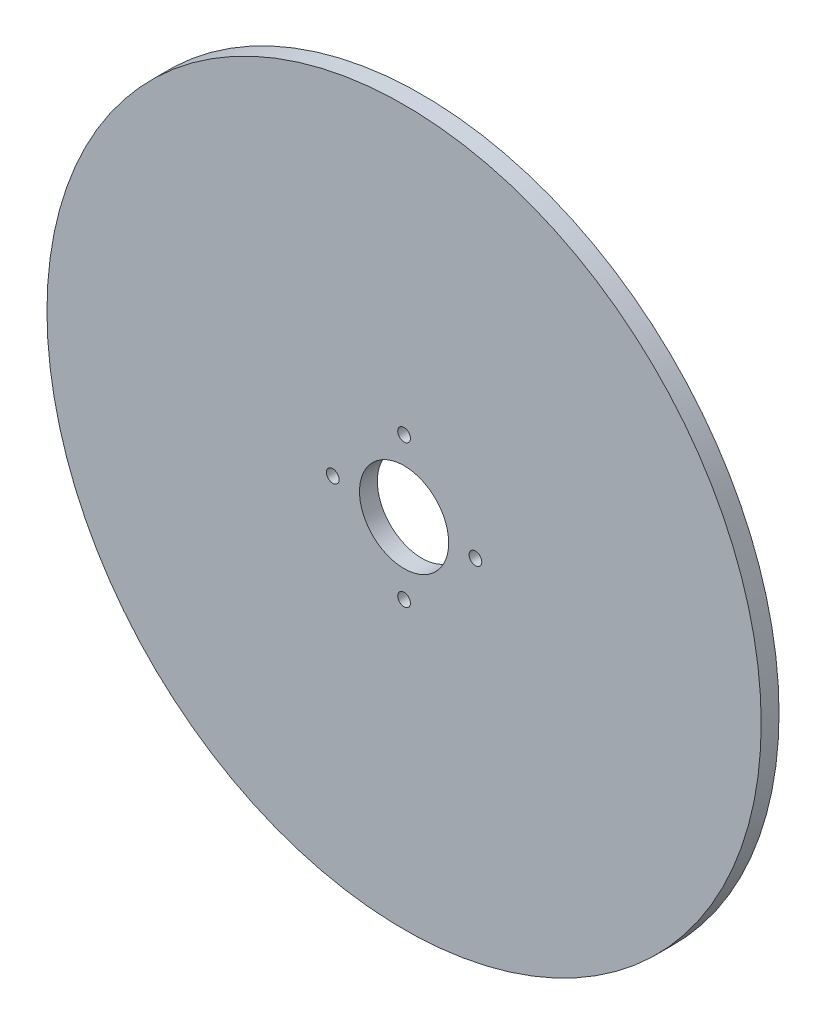
SolidWorks part; units mm, degrees
material "6061 Alloy"
ref_plane "Front Plane" through (0, 0, 0) normal (0, 0, 1) x (1, 0, 0)
ref_plane "Top Plane" through (0, 0, 0) normal (0, 1, 0) x (1, 0, 0)
ref_plane "Right Plane" through (0, 0, 0) normal (1, 0, 0) x (0, 0, -1)
sketch "Sketch1" plane through (0, 0, 0) normal (0, 0, 1) x (1, 0, 0)
  circle A0 centre (0, 0) radius 63.5762
  circle A1 centre (0, 0) radius 7.9375
  dimension "D1" = 127.1524
  dimension "D2" = 15.875
extrude "Boss-Extrude1" add sketch "Sketch1" along normal blind 3.175
hole_wizard "Tap Drill for #4-40 Tap1" positions "Sketch2" profile "Sketch3" hole size "#4-40" standard "ANSI Inch"
sketch "Sketch2" plane through (0, 0, 3.175) normal (0, 0, 1) x (1, 0, 0)
  point P0 (0, 12.7)
  point P2 (0, -12.7)
  point P4 (12.7, 0)
  point P6 (-12.7, 0)
  dimension "D1" = 12.7
  dimension "D2" = 12.7
  dimension "D3" = 12.7
  dimension "D4" = 12.7
sketch "Sketch3" plane through (0, 12.7, 3.175) normal (1, 0, 0) x (0, -1, 0)
  line L0 (0, 0) -> (0, 4.6792)
  line L1 (0, 4.6792) -> (1.1303, 4)
  line L2 (1.1303, 4) -> (1.1303, 0)
  line L5 (1.1303, 0) -> (0, 0)
  line L10 (0, 4.6792) -> (-1.1303, 4) construction
  line L11 (0, -6.35) -> (0, 107.95) construction
  dimension "Hole Dia." = 2.2606
  dimension "Hole Depth" = 4
  dimension "Drill Angle" = 118
